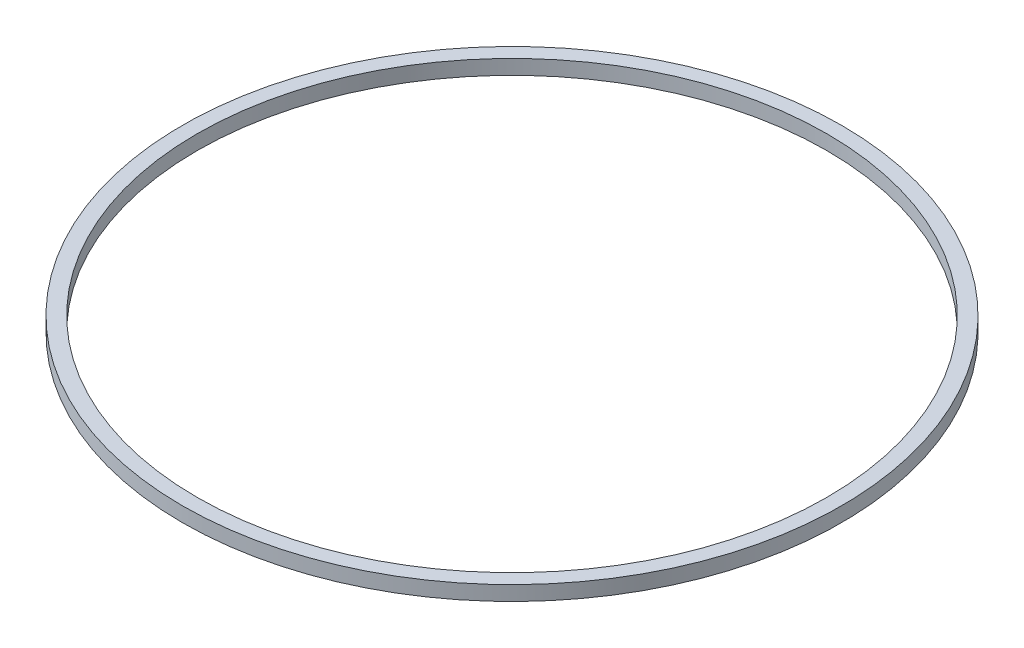
SolidWorks part; units mm, degrees
ref_plane "Front Plane" through (0, 0, 0) normal (0, 0, 1) x (1, 0, 0)
ref_plane "Top Plane" through (0, 0, 0) normal (0, 1, 0) x (1, 0, 0)
ref_plane "Right Plane" through (0, 0, 0) normal (1, 0, 0) x (0, 0, -1)
sketch "Sketch1" plane through (0, 0, 0) normal (0, 1, 0) x (1, 0, 0)
  circle A0 centre (0, 0) radius 225
  dimension "D1" = 450
extrude "Boss-Extrude1" add sketch "Sketch1" along normal blind 10
sketch "Sketch2" plane through (0, 10, 0) normal (0, 1, 0) x (1, 0, 0)
  circle A2 centre (0, 0) radius 215
  circle A3 centre (0, 0) radius 215
  dimension "D1" = 10
extrude "Cut-Extrude1" cut sketch "Sketch2" against normal through all
